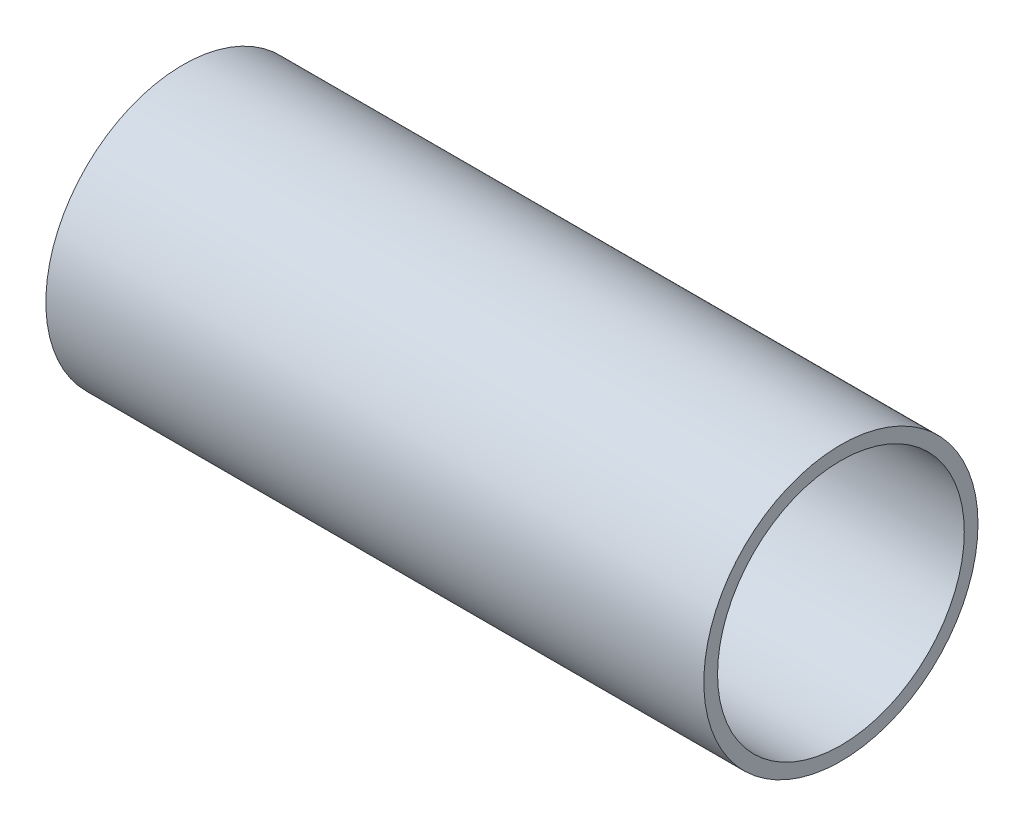
SolidWorks part; units mm, degrees
material "6061 Alloy"
ref_plane "Front Plane" through (0, 0, 0) normal (0, 0, 1) x (1, 0, 0)
ref_plane "Top Plane" through (0, 0, 0) normal (0, 1, 0) x (1, 0, 0)
ref_plane "Right Plane" through (0, 0, 0) normal (1, 0, 0) x (0, 0, -1)
sketch "Sketch2" plane through (0, 0, 0) normal (1, 0, 0) x (0, 0, -1)
  circle A0 centre (0, 0) radius 25
  circle A1 centre (0, 0) radius 22.5
  dimension "D1" = 50
  dimension "D2" = 45
extrude "Boss-Extrude1" add sketch "Sketch2" along normal blind 120
